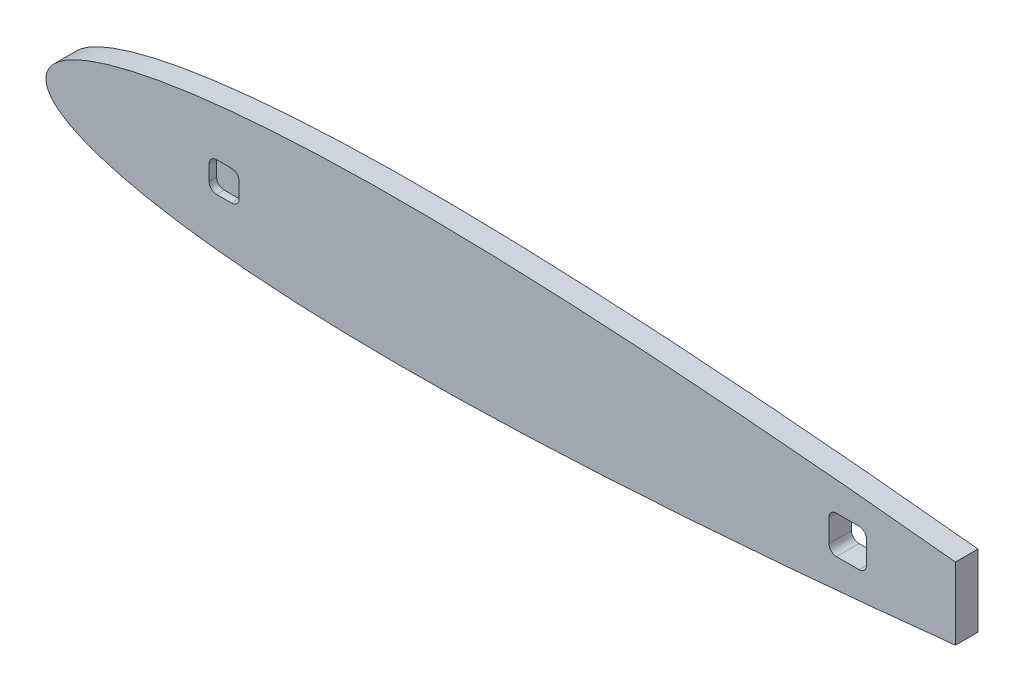
SolidWorks part; units mm, degrees
ref_plane "Plano frontal" through (0, 0, 0) normal (0, 0, 1) x (1, 0, 0)
ref_plane "Plano superior" through (0, 0, 0) normal (0, 1, 0) x (1, 0, 0)
ref_plane "Plano direito" through (0, 0, 0) normal (1, 0, 0) x (0, 0, -1)
curve "1"
  spline degree 3 poles (318.017, -0.275, 0) (321.8619, 0, 0) (318.017, 0.275, 0) (316.8488, 0.4429, 0) (316.2887, 0.5205, 0) (315.3688, 0.6495, 0) (314.0783, 0.829, 0) (312.4264, 1.0569, 0) (310.4146, 1.3335, 0) (308.0483, 1.6557, 0) (305.3328, 2.0216, 0) (302.2747, 2.4296, 0) (298.881, 2.8766, 0) (295.1596, 3.3607, 0) (291.1192, 3.8779, 0) (286.7692, 4.4269, 0) (282.1198, 5.0039, 0) (277.1818, 5.6059, 0) (271.9669, 6.2303, 0) (266.4872, 6.8736, 0) (260.7553, 7.5322, 0) (254.7848, 8.2043, 0) (248.5896, 8.8851, 0) (242.1844, 9.5727, 0) (235.5837, 10.2623, 0) (228.8033, 10.9526, 0) (221.8588, 11.6382, 0) (214.7666, 12.3171, 0) (207.5431, 12.9844, 0) (200.2052, 13.638, 0) (192.77, 14.2725, 0) (185.255, 14.885, 0) (177.6777, 15.4717, 0) (170.0557, 16.0279, 0) (162.407, 16.55, 0) (154.7495, 17.0338, 0) (147.1007, 17.4748, 0) (139.4788, 17.8694, 0) (131.9014, 18.2133, 0) (124.3862, 18.5027, 0) (116.9509, 18.7344, 0) (109.6128, 18.9042, 0) (102.389, 19.0091, 0) (95.2963, 19.0463, 0) (88.3513, 19.0134, 0) (81.5703, 18.9091, 0) (74.9692, 18.7301, 0) (68.5632, 18.4773, 0) (62.3674, 18.1489, 0) (56.396, 17.7457, 0) (50.6632, 17.2678, 0) (45.1824, 16.7162, 0) (39.9662, 16.0928, 0) (35.0266, 15.4003, 0) (30.3754, 14.64, 0) (26.0232, 13.8155, 0) (21.9799, 12.9301, 0) (18.2551, 11.9867, 0) (14.8569, 10.9896, 0) (11.7929, 9.9421, 0) (9.0696, 8.8477, 0) (6.6923, 7.7097, 0) (4.6657, 6.5304, 0) (2.9921, 5.3119, 0) (1.6746, 4.052, 0) (0.7166, 2.7472, 0) (0.1308, 1.3913, 0) (-0.0638, 0, 0) (0.1308, -1.3913, 0) (0.7166, -2.7472, 0) (1.6746, -4.052, 0) (2.9921, -5.3119, 0) (4.6657, -6.5304, 0) (6.6923, -7.7097, 0) (9.0696, -8.8477, 0) (11.7929, -9.9421, 0) (14.8569, -10.9896, 0) (18.2551, -11.9867, 0) (21.9799, -12.9301, 0) (26.0232, -13.8155, 0) (30.3754, -14.64, 0) (35.0266, -15.4003, 0) (39.9662, -16.0928, 0) (45.1824, -16.7162, 0) (50.6632, -17.2678, 0) (56.396, -17.7457, 0) (62.3674, -18.1489, 0) (68.5632, -18.4773, 0) (74.9692, -18.7301, 0) (81.5703, -18.9091, 0) (88.3513, -19.0134, 0) (95.2963, -19.0463, 0) (102.389, -19.0091, 0) (109.6128, -18.9042, 0) (116.9509, -18.7344, 0) (124.3862, -18.5027, 0) (131.9014, -18.2133, 0) (139.4788, -17.8694, 0) (147.1007, -17.4748, 0) (154.7495, -17.0338, 0) (162.407, -16.55, 0) (170.0557, -16.0279, 0) (177.6777, -15.4717, 0) (185.255, -14.885, 0) (192.77, -14.2725, 0) (200.2052, -13.638, 0) (207.5431, -12.9844, 0) (214.7666, -12.3171, 0) (221.8588, -11.6382, 0) (228.8033, -10.9526, 0) (235.5837, -10.2623, 0) (242.1844, -9.5727, 0) (248.5896, -8.8851, 0) (254.7848, -8.2043, 0) (260.7553, -7.5322, 0) (266.4872, -6.8736, 0) (271.9669, -6.2303, 0) (277.1818, -5.6059, 0) (282.1198, -5.0039, 0) (286.7692, -4.4269, 0) (291.1192, -3.8779, 0) (295.1596, -3.3607, 0) (298.881, -2.8766, 0) (302.2747, -2.4296, 0) (305.3328, -2.0216, 0) (308.0483, -1.6557, 0) (310.4146, -1.3335, 0) (312.4264, -1.0569, 0) (314.0783, -0.829, 0) (315.3688, -0.6495, 0) (316.2887, -0.5205, 0) (316.8488, -0.4429, 0) (318.017, -0.275, 0) (321.8619, 0, 0) (318.017, 0.275, 0) knots -0.00555 -0.004691 -0.004405 0 0.004405 0.004691 0.00555 0.00698 0.008976 0.011535 0.014649 0.018312 0.022515 0.027248 0.032498 0.038254 0.044502 0.051227 0.058413 0.066043 0.074099 0.082562 0.091412 0.100627 0.110187 0.120068 0.130247 0.140701 0.151404 0.162332 0.173459 0.184758 0.196204 0.207769 0.219426 0.231148 0.242906 0.254675 0.266426 0.278132 0.289766 0.301302 0.312712 0.323969 0.33505 0.345929 0.356581 0.366982 0.37711 0.386942 0.396458 0.405637 0.414459 0.422907 0.430963 0.438612 0.445838 0.45263 0.458976 0.464866 0.470294 0.475255 0.479749 0.483781 0.487363 0.490516 0.493279 0.495712 0.49791 0.5 0.50209 0.504288 0.506721 0.509484 0.512637 0.516219 0.520251 0.524745 0.529706 0.535134 0.541024 0.54737 0.554162 0.561388 0.569037 0.577093 0.585541 0.594363 0.603542 0.613058 0.62289 0.633018 0.643419 0.654071 0.66495 0.676031 0.687288 0.698698 0.710234 0.721868 0.733574 0.745325 0.757094 0.768852 0.780574 0.792231 0.803796 0.815242 0.826541 0.837668 0.848596 0.859299 0.869753 0.879932 0.889813 0.899373 0.908588 0.917438 0.925901 0.933957 0.941587 0.948773 0.955498 0.961746 0.967502 0.972752 0.977485 0.981688 0.985351 0.988465 0.991024 0.99302 0.99445 0.995309 0.995595 1 1.004405 1.004691 1.00555 periodic
curve "3"
  spline degree 3 poles (285.8178, -0.2472, 0) (289.2733, 0, 0) (285.8178, 0.2472, 0) (284.7679, 0.3981, 0) (284.2644, 0.4678, 0) (283.4377, 0.5838, 0) (282.2778, 0.7451, 0) (280.7932, 0.9499, 0) (278.9851, 1.1985, 0) (276.8584, 1.4881, 0) (274.4179, 1.8169, 0) (271.6694, 2.1836, 0) (268.6193, 2.5853, 0) (265.2747, 3.0204, 0) (261.6434, 3.4852, 0) (257.7338, 3.9787, 0) (253.5551, 4.4973, 0) (249.1172, 5.0383, 0) (244.4303, 5.5995, 0) (239.5054, 6.1777, 0) (234.3538, 6.7696, 0) (228.9879, 7.3736, 0) (223.4199, 7.9855, 0) (217.6632, 8.6035, 0) (211.7309, 9.2233, 0) (205.637, 9.8437, 0) (199.3956, 10.4599, 0) (193.0214, 11.07, 0) (186.5293, 11.6697, 0) (179.9344, 12.2571, 0) (173.2521, 12.8274, 0) (166.4979, 13.3779, 0) (159.6878, 13.9052, 0) (152.8376, 14.4051, 0) (145.9633, 14.8743, 0) (139.0811, 15.3092, 0) (132.2068, 15.7055, 0) (125.3566, 16.0601, 0) (118.5464, 16.3692, 0) (111.7921, 16.6293, 0) (105.1096, 16.8375, 0) (98.5145, 16.9901, 0) (92.0222, 17.0845, 0) (85.6476, 17.1179, 0) (79.4058, 17.0883, 0) (73.3113, 16.9946, 0) (67.3786, 16.8337, 0) (61.6212, 16.6065, 0) (56.0527, 16.3113, 0) (50.6859, 15.9489, 0) (45.5336, 15.5194, 0) (40.6077, 15.0237, 0) (35.9196, 14.4634, 0) (31.4802, 13.841, 0) (27.2999, 13.1577, 0) (23.3883, 12.4167, 0) (19.7544, 11.6209, 0) (16.4067, 10.7731, 0) (13.3526, 9.8769, 0) (10.5989, 8.9355, 0) (8.1513, 7.9519, 0) (6.0147, 6.9291, 0) (4.1933, 5.8692, 0) (2.6891, 4.774, 0) (1.5051, 3.6417, 0) (0.644, 2.4691, 0) (0.1176, 1.2504, 0) (-0.0573, 0, 0) (0.1176, -1.2504, 0) (0.644, -2.4691, 0) (1.5051, -3.6417, 0) (2.6891, -4.774, 0) (4.1933, -5.8692, 0) (6.0147, -6.9291, 0) (8.1513, -7.9519, 0) (10.5989, -8.9355, 0) (13.3526, -9.8769, 0) (16.4067, -10.7731, 0) (19.7544, -11.6209, 0) (23.3883, -12.4167, 0) (27.2999, -13.1577, 0) (31.4802, -13.841, 0) (35.9196, -14.4634, 0) (40.6077, -15.0237, 0) (45.5336, -15.5194, 0) (50.6859, -15.9489, 0) (56.0527, -16.3113, 0) (61.6212, -16.6065, 0) (67.3786, -16.8337, 0) (73.3113, -16.9946, 0) (79.4058, -17.0883, 0) (85.6476, -17.1179, 0) (92.0222, -17.0845, 0) (98.5145, -16.9901, 0) (105.1096, -16.8375, 0) (111.7921, -16.6293, 0) (118.5464, -16.3692, 0) (125.3566, -16.0601, 0) (132.2068, -15.7055, 0) (139.0811, -15.3092, 0) (145.9633, -14.8743, 0) (152.8376, -14.4051, 0) (159.6878, -13.9052, 0) (166.4979, -13.3779, 0) (173.2521, -12.8274, 0) (179.9344, -12.2571, 0) (186.5293, -11.6697, 0) (193.0214, -11.07, 0) (199.3956, -10.4599, 0) (205.637, -9.8437, 0) (211.7309, -9.2233, 0) (217.6632, -8.6035, 0) (223.4199, -7.9855, 0) (228.9879, -7.3736, 0) (234.3538, -6.7696, 0) (239.5054, -6.1777, 0) (244.4303, -5.5995, 0) (249.1172, -5.0383, 0) (253.5551, -4.4973, 0) (257.7338, -3.9787, 0) (261.6434, -3.4852, 0) (265.2747, -3.0204, 0) (268.6193, -2.5853, 0) (271.6694, -2.1836, 0) (274.4179, -1.8169, 0) (276.8584, -1.4881, 0) (278.9851, -1.1985, 0) (280.7932, -0.9499, 0) (282.2778, -0.7451, 0) (283.4377, -0.5838, 0) (284.2644, -0.4678, 0) (284.7679, -0.3981, 0) (285.8178, -0.2472, 0) (289.2733, 0, 0) (285.8178, 0.2472, 0) knots -0.00555 -0.004691 -0.004405 0 0.004405 0.004691 0.00555 0.00698 0.008976 0.011535 0.014649 0.018312 0.022515 0.027248 0.032498 0.038254 0.044502 0.051227 0.058413 0.066043 0.074099 0.082562 0.091412 0.100627 0.110187 0.120068 0.130247 0.140701 0.151404 0.162332 0.173459 0.184758 0.196204 0.207769 0.219426 0.231148 0.242906 0.254675 0.266426 0.278132 0.289766 0.301302 0.312712 0.323969 0.33505 0.345929 0.356581 0.366982 0.37711 0.386942 0.396458 0.405637 0.414459 0.422907 0.430963 0.438612 0.445838 0.45263 0.458976 0.464866 0.470294 0.475255 0.479749 0.483781 0.487363 0.490516 0.493279 0.495712 0.49791 0.5 0.50209 0.504288 0.506721 0.509484 0.512637 0.516219 0.520251 0.524745 0.529706 0.535134 0.541024 0.54737 0.554162 0.561388 0.569037 0.577093 0.585541 0.594363 0.603542 0.613058 0.62289 0.633018 0.643419 0.654071 0.66495 0.676031 0.687288 0.698698 0.710234 0.721868 0.733574 0.745325 0.757094 0.768852 0.780574 0.792231 0.803796 0.815242 0.826541 0.837668 0.848596 0.859299 0.869753 0.879932 0.889813 0.899373 0.908588 0.917438 0.925901 0.933957 0.941587 0.948773 0.955498 0.961746 0.967502 0.972752 0.977485 0.981688 0.985351 0.988465 0.991024 0.99302 0.99445 0.995309 0.995595 1 1.004405 1.004691 1.00555 periodic
sketch "1-3" plane through (0, 0, 0) normal (0, 0, 1) x (1, 0, 0)
  line L0 (320, 0) -> (287.6, 0) construction
  spline S0 degree 3 poles (285.8178, -0.2472) (289.2733, 0) (285.8178, 0.2472) (284.7679, 0.3981) (284.2644, 0.4678) (283.4377, 0.5838) (282.2778, 0.7451) (280.7932, 0.9499) (278.9851, 1.1985) (276.8584, 1.4881) (274.4179, 1.8169) (271.6694, 2.1836) (268.6193, 2.5853) (265.2747, 3.0204) (261.6434, 3.4852) (257.7338, 3.9787) (253.5551, 4.4973) (249.1172, 5.0383) (244.4303, 5.5995) (239.5054, 6.1777) (234.3538, 6.7696) (228.9879, 7.3736) (223.4199, 7.9855) (217.6632, 8.6035) (211.7309, 9.2233) (205.637, 9.8437) (199.3956, 10.4599) (193.0214, 11.07) (186.5293, 11.6697) (179.9344, 12.2571) (173.2521, 12.8274) (166.4979, 13.3779) (159.6878, 13.9052) (152.8376, 14.4051) (145.9633, 14.8743) (139.0811, 15.3092) (132.2068, 15.7055) (125.3566, 16.0601) (118.5464, 16.3692) (111.7921, 16.6293) (105.1096, 16.8375) (98.5145, 16.9901) (92.0222, 17.0845) (85.6476, 17.1179) (79.4058, 17.0883) (73.3113, 16.9946) (67.3786, 16.8337) (61.6212, 16.6065) (56.0527, 16.3113) (50.6859, 15.9489) (45.5336, 15.5194) (40.6077, 15.0237) (35.9196, 14.4634) (31.4802, 13.841) (27.2999, 13.1577) (23.3883, 12.4167) (19.7544, 11.6209) (16.4067, 10.7731) (13.3526, 9.8769) (10.5989, 8.9355) (8.1513, 7.9519) (6.0147, 6.9291) (4.1933, 5.8692) (2.6891, 4.774) (1.5051, 3.6417) (0.644, 2.4691) (0.1176, 1.2504) (-0.0573, 0) (0.1176, -1.2504) (0.644, -2.4691) (1.5051, -3.6417) (2.6891, -4.774) (4.1933, -5.8692) (6.0147, -6.9291) (8.1513, -7.9519) (10.5989, -8.9355) (13.3526, -9.8769) (16.4067, -10.7731) (19.7544, -11.6209) (23.3883, -12.4167) (27.2999, -13.1577) (31.4802, -13.841) (35.9196, -14.4634) (40.6077, -15.0237) (45.5336, -15.5194) (50.6859, -15.9489) (56.0527, -16.3113) (61.6212, -16.6065) (67.3786, -16.8337) (73.3113, -16.9946) (79.4058, -17.0883) (85.6476, -17.1179) (92.0222, -17.0845) (98.5145, -16.9901) (105.1096, -16.8375) (111.7921, -16.6293) (118.5464, -16.3692) (125.3566, -16.0601) (132.2068, -15.7055) (139.0811, -15.3092) (145.9633, -14.8743) (152.8376, -14.4051) (159.6878, -13.9052) (166.4979, -13.3779) (173.2521, -12.8274) (179.9344, -12.2571) (186.5293, -11.6697) (193.0214, -11.07) (199.3956, -10.4599) (205.637, -9.8437) (211.7309, -9.2233) (217.6632, -8.6035) (223.4199, -7.9855) (228.9879, -7.3736) (234.3538, -6.7696) (239.5054, -6.1777) (244.4303, -5.5995) (249.1172, -5.0383) (253.5551, -4.4973) (257.7338, -3.9787) (261.6434, -3.4852) (265.2747, -3.0204) (268.6193, -2.5853) (271.6694, -2.1836) (274.4179, -1.8169) (276.8584, -1.4881) (278.9851, -1.1985) (280.7932, -0.9499) (282.2778, -0.7451) (283.4377, -0.5838) (284.2644, -0.4678) (284.7679, -0.3981) (285.8178, -0.2472) (289.2733, 0) (285.8178, 0.2472) knots -0.00555 -0.004691 -0.004405 0 0.004405 0.004691 0.00555 0.00698 0.008976 0.011535 0.014649 0.018312 0.022515 0.027248 0.032498 0.038254 0.044502 0.051227 0.058413 0.066043 0.074099 0.082562 0.091412 0.100627 0.110187 0.120068 0.130247 0.140701 0.151404 0.162332 0.173459 0.184758 0.196204 0.207769 0.219426 0.231148 0.242906 0.254675 0.266426 0.278132 0.289766 0.301302 0.312712 0.323969 0.33505 0.345929 0.356581 0.366982 0.37711 0.386942 0.396458 0.405637 0.414459 0.422907 0.430963 0.438612 0.445838 0.45263 0.458976 0.464866 0.470294 0.475255 0.479749 0.483781 0.487363 0.490516 0.493279 0.495712 0.49791 0.5 0.50209 0.504288 0.506721 0.509484 0.512637 0.516219 0.520251 0.524745 0.529706 0.535134 0.541024 0.54737 0.554162 0.561388 0.569037 0.577093 0.585541 0.594363 0.603542 0.613058 0.62289 0.633018 0.643419 0.654071 0.66495 0.676031 0.687288 0.698698 0.710234 0.721868 0.733574 0.745325 0.757094 0.768852 0.780574 0.792231 0.803796 0.815242 0.826541 0.837668 0.848596 0.859299 0.869753 0.879932 0.889813 0.899373 0.908588 0.917438 0.925901 0.933957 0.941587 0.948773 0.955498 0.961746 0.967502 0.972752 0.977485 0.981688 0.985351 0.988465 0.991024 0.99302 0.99445 0.995309 0.995595 1 1.004405 1.004691 1.00555 only from (287.6, 0) to (287.6, 0) construction
  spline S1 degree 3 poles (318.017, -0.275) (321.8619, 0) (318.017, 0.275) (316.8488, 0.4429) (316.2887, 0.5205) (315.3688, 0.6495) (314.0783, 0.829) (312.4264, 1.0569) (310.4146, 1.3335) (308.0483, 1.6557) (305.3328, 2.0216) (302.2747, 2.4296) (298.881, 2.8766) (295.1596, 3.3607) (291.1192, 3.8779) (286.7692, 4.4269) (282.1198, 5.0039) (277.1818, 5.6059) (271.9669, 6.2303) (266.4872, 6.8736) (260.7553, 7.5322) (254.7848, 8.2043) (248.5896, 8.8851) (242.1844, 9.5727) (235.5837, 10.2623) (228.8033, 10.9526) (221.8588, 11.6382) (214.7666, 12.3171) (207.5431, 12.9844) (200.2052, 13.638) (192.77, 14.2725) (185.255, 14.885) (177.6777, 15.4717) (170.0557, 16.0279) (162.407, 16.55) (154.7495, 17.0338) (147.1007, 17.4748) (139.4788, 17.8694) (131.9014, 18.2133) (124.3862, 18.5027) (116.9509, 18.7344) (109.6128, 18.9042) (102.389, 19.0091) (95.2963, 19.0463) (88.3513, 19.0134) (81.5703, 18.9091) (74.9692, 18.7301) (68.5632, 18.4773) (62.3674, 18.1489) (56.396, 17.7457) (50.6632, 17.2678) (45.1824, 16.7162) (39.9662, 16.0928) (35.0266, 15.4003) (30.3754, 14.64) (26.0232, 13.8155) (21.9799, 12.9301) (18.2551, 11.9867) (14.8569, 10.9896) (11.7929, 9.9421) (9.0696, 8.8477) (6.6923, 7.7097) (4.6657, 6.5304) (2.9921, 5.3119) (1.6746, 4.052) (0.7166, 2.7472) (0.1308, 1.3913) (-0.0638, 0) (0.1308, -1.3913) (0.7166, -2.7472) (1.6746, -4.052) (2.9921, -5.3119) (4.6657, -6.5304) (6.6923, -7.7097) (9.0696, -8.8477) (11.7929, -9.9421) (14.8569, -10.9896) (18.2551, -11.9867) (21.9799, -12.9301) (26.0232, -13.8155) (30.3754, -14.64) (35.0266, -15.4003) (39.9662, -16.0928) (45.1824, -16.7162) (50.6632, -17.2678) (56.396, -17.7457) (62.3674, -18.1489) (68.5632, -18.4773) (74.9692, -18.7301) (81.5703, -18.9091) (88.3513, -19.0134) (95.2963, -19.0463) (102.389, -19.0091) (109.6128, -18.9042) (116.9509, -18.7344) (124.3862, -18.5027) (131.9014, -18.2133) (139.4788, -17.8694) (147.1007, -17.4748) (154.7495, -17.0338) (162.407, -16.55) (170.0557, -16.0279) (177.6777, -15.4717) (185.255, -14.885) (192.77, -14.2725) (200.2052, -13.638) (207.5431, -12.9844) (214.7666, -12.3171) (221.8588, -11.6382) (228.8033, -10.9526) (235.5837, -10.2623) (242.1844, -9.5727) (248.5896, -8.8851) (254.7848, -8.2043) (260.7553, -7.5322) (266.4872, -6.8736) (271.9669, -6.2303) (277.1818, -5.6059) (282.1198, -5.0039) (286.7692, -4.4269) (291.1192, -3.8779) (295.1596, -3.3607) (298.881, -2.8766) (302.2747, -2.4296) (305.3328, -2.0216) (308.0483, -1.6557) (310.4146, -1.3335) (312.4264, -1.0569) (314.0783, -0.829) (315.3688, -0.6495) (316.2887, -0.5205) (316.8488, -0.4429) (318.017, -0.275) (321.8619, 0) (318.017, 0.275) knots -0.00555 -0.004691 -0.004405 0 0.004405 0.004691 0.00555 0.00698 0.008976 0.011535 0.014649 0.018312 0.022515 0.027248 0.032498 0.038254 0.044502 0.051227 0.058413 0.066043 0.074099 0.082562 0.091412 0.100627 0.110187 0.120068 0.130247 0.140701 0.151404 0.162332 0.173459 0.184758 0.196204 0.207769 0.219426 0.231148 0.242906 0.254675 0.266426 0.278132 0.289766 0.301302 0.312712 0.323969 0.33505 0.345929 0.356581 0.366982 0.37711 0.386942 0.396458 0.405637 0.414459 0.422907 0.430963 0.438612 0.445838 0.45263 0.458976 0.464866 0.470294 0.475255 0.479749 0.483781 0.487363 0.490516 0.493279 0.495712 0.49791 0.5 0.50209 0.504288 0.506721 0.509484 0.512637 0.516219 0.520251 0.524745 0.529706 0.535134 0.541024 0.54737 0.554162 0.561388 0.569037 0.577093 0.585541 0.594363 0.603542 0.613058 0.62289 0.633018 0.643419 0.654071 0.66495 0.676031 0.687288 0.698698 0.710234 0.721868 0.733574 0.745325 0.757094 0.768852 0.780574 0.792231 0.803796 0.815242 0.826541 0.837668 0.848596 0.859299 0.869753 0.879932 0.889813 0.899373 0.908588 0.917438 0.925901 0.933957 0.941587 0.948773 0.955498 0.961746 0.967502 0.972752 0.977485 0.981688 0.985351 0.988465 0.991024 0.99302 0.99445 0.995309 0.995595 1 1.004405 1.004691 1.00555 only from (320, 0) to (320, 0) construction
  spline S2 degree 3 poles (285.8178, -0.2472) (289.2733, 0) (285.8178, 0.2472) (284.7679, 0.3981) (284.2644, 0.4678) (283.4377, 0.5838) (282.2778, 0.7451) (280.7932, 0.9499) (278.9851, 1.1985) (276.8584, 1.4881) (274.4179, 1.8169) (271.6694, 2.1836) (268.6193, 2.5853) (265.2747, 3.0204) (261.6434, 3.4852) (257.7338, 3.9787) (253.5551, 4.4973) (249.1172, 5.0383) (244.4303, 5.5995) (239.5054, 6.1777) (234.3538, 6.7696) (228.9879, 7.3736) (223.4199, 7.9855) (217.6632, 8.6035) (211.7309, 9.2233) (205.637, 9.8437) (199.3956, 10.4599) (193.0214, 11.07) (186.5293, 11.6697) (179.9344, 12.2571) (173.2521, 12.8274) (166.4979, 13.3779) (159.6878, 13.9052) (152.8376, 14.4051) (145.9633, 14.8743) (139.0811, 15.3092) (132.2068, 15.7055) (125.3566, 16.0601) (118.5464, 16.3692) (111.7921, 16.6293) (105.1096, 16.8375) (98.5145, 16.9901) (92.0222, 17.0845) (85.6476, 17.1179) (79.4058, 17.0883) (73.3113, 16.9946) (67.3786, 16.8337) (61.6212, 16.6065) (56.0527, 16.3113) (50.6859, 15.9489) (45.5336, 15.5194) (40.6077, 15.0237) (35.9196, 14.4634) (31.4802, 13.841) (27.2999, 13.1577) (23.3883, 12.4167) (19.7544, 11.6209) (16.4067, 10.7731) (13.3526, 9.8769) (10.5989, 8.9355) (8.1513, 7.9519) (6.0147, 6.9291) (4.1933, 5.8692) (2.6891, 4.774) (1.5051, 3.6417) (0.644, 2.4691) (0.1176, 1.2504) (-0.0573, 0) (0.1176, -1.2504) (0.644, -2.4691) (1.5051, -3.6417) (2.6891, -4.774) (4.1933, -5.8692) (6.0147, -6.9291) (8.1513, -7.9519) (10.5989, -8.9355) (13.3526, -9.8769) (16.4067, -10.7731) (19.7544, -11.6209) (23.3883, -12.4167) (27.2999, -13.1577) (31.4802, -13.841) (35.9196, -14.4634) (40.6077, -15.0237) (45.5336, -15.5194) (50.6859, -15.9489) (56.0527, -16.3113) (61.6212, -16.6065) (67.3786, -16.8337) (73.3113, -16.9946) (79.4058, -17.0883) (85.6476, -17.1179) (92.0222, -17.0845) (98.5145, -16.9901) (105.1096, -16.8375) (111.7921, -16.6293) (118.5464, -16.3692) (125.3566, -16.0601) (132.2068, -15.7055) (139.0811, -15.3092) (145.9633, -14.8743) (152.8376, -14.4051) (159.6878, -13.9052) (166.4979, -13.3779) (173.2521, -12.8274) (179.9344, -12.2571) (186.5293, -11.6697) (193.0214, -11.07) (199.3956, -10.4599) (205.637, -9.8437) (211.7309, -9.2233) (217.6632, -8.6035) (223.4199, -7.9855) (228.9879, -7.3736) (234.3538, -6.7696) (239.5054, -6.1777) (244.4303, -5.5995) (249.1172, -5.0383) (253.5551, -4.4973) (257.7338, -3.9787) (261.6434, -3.4852) (265.2747, -3.0204) (268.6193, -2.5853) (271.6694, -2.1836) (274.4179, -1.8169) (276.8584, -1.4881) (278.9851, -1.1985) (280.7932, -0.9499) (282.2778, -0.7451) (283.4377, -0.5838) (284.2644, -0.4678) (284.7679, -0.3981) (285.8178, -0.2472) (289.2733, 0) (285.8178, 0.2472) knots -0.00555 -0.004691 -0.004405 0 0.004405 0.004691 0.00555 0.00698 0.008976 0.011535 0.014649 0.018312 0.022515 0.027248 0.032498 0.038254 0.044502 0.051227 0.058413 0.066043 0.074099 0.082562 0.091412 0.100627 0.110187 0.120068 0.130247 0.140701 0.151404 0.162332 0.173459 0.184758 0.196204 0.207769 0.219426 0.231148 0.242906 0.254675 0.266426 0.278132 0.289766 0.301302 0.312712 0.323969 0.33505 0.345929 0.356581 0.366982 0.37711 0.386942 0.396458 0.405637 0.414459 0.422907 0.430963 0.438612 0.445838 0.45263 0.458976 0.464866 0.470294 0.475255 0.479749 0.483781 0.487363 0.490516 0.493279 0.495712 0.49791 0.5 0.50209 0.504288 0.506721 0.509484 0.512637 0.516219 0.520251 0.524745 0.529706 0.535134 0.541024 0.54737 0.554162 0.561388 0.569037 0.577093 0.585541 0.594363 0.603542 0.613058 0.62289 0.633018 0.643419 0.654071 0.66495 0.676031 0.687288 0.698698 0.710234 0.721868 0.733574 0.745325 0.757094 0.768852 0.780574 0.792231 0.803796 0.815242 0.826541 0.837668 0.848596 0.859299 0.869753 0.879932 0.889813 0.899373 0.908588 0.917438 0.925901 0.933957 0.941587 0.948773 0.955498 0.961746 0.967502 0.972752 0.977485 0.981688 0.985351 0.988465 0.991024 0.99302 0.99445 0.995309 0.995595 1 1.004405 1.004691 1.00555 only from (287.6, 0) to (287.6, 0)
  spline S3 degree 3 poles (318.017, -0.275) (321.8619, 0) (318.017, 0.275) (316.8488, 0.4429) (316.2887, 0.5205) (315.3688, 0.6495) (314.0783, 0.829) (312.4264, 1.0569) (310.4146, 1.3335) (308.0483, 1.6557) (305.3328, 2.0216) (302.2747, 2.4296) (298.881, 2.8766) (295.1596, 3.3607) (291.1192, 3.8779) (286.7692, 4.4269) (282.1198, 5.0039) (277.1818, 5.6059) (271.9669, 6.2303) (266.4872, 6.8736) (260.7553, 7.5322) (254.7848, 8.2043) (248.5896, 8.8851) (242.1844, 9.5727) (235.5837, 10.2623) (228.8033, 10.9526) (221.8588, 11.6382) (214.7666, 12.3171) (207.5431, 12.9844) (200.2052, 13.638) (192.77, 14.2725) (185.255, 14.885) (177.6777, 15.4717) (170.0557, 16.0279) (162.407, 16.55) (154.7495, 17.0338) (147.1007, 17.4748) (139.4788, 17.8694) (131.9014, 18.2133) (124.3862, 18.5027) (116.9509, 18.7344) (109.6128, 18.9042) (102.389, 19.0091) (95.2963, 19.0463) (88.3513, 19.0134) (81.5703, 18.9091) (74.9692, 18.7301) (68.5632, 18.4773) (62.3674, 18.1489) (56.396, 17.7457) (50.6632, 17.2678) (45.1824, 16.7162) (39.9662, 16.0928) (35.0266, 15.4003) (30.3754, 14.64) (26.0232, 13.8155) (21.9799, 12.9301) (18.2551, 11.9867) (14.8569, 10.9896) (11.7929, 9.9421) (9.0696, 8.8477) (6.6923, 7.7097) (4.6657, 6.5304) (2.9921, 5.3119) (1.6746, 4.052) (0.7166, 2.7472) (0.1308, 1.3913) (-0.0638, 0) (0.1308, -1.3913) (0.7166, -2.7472) (1.6746, -4.052) (2.9921, -5.3119) (4.6657, -6.5304) (6.6923, -7.7097) (9.0696, -8.8477) (11.7929, -9.9421) (14.8569, -10.9896) (18.2551, -11.9867) (21.9799, -12.9301) (26.0232, -13.8155) (30.3754, -14.64) (35.0266, -15.4003) (39.9662, -16.0928) (45.1824, -16.7162) (50.6632, -17.2678) (56.396, -17.7457) (62.3674, -18.1489) (68.5632, -18.4773) (74.9692, -18.7301) (81.5703, -18.9091) (88.3513, -19.0134) (95.2963, -19.0463) (102.389, -19.0091) (109.6128, -18.9042) (116.9509, -18.7344) (124.3862, -18.5027) (131.9014, -18.2133) (139.4788, -17.8694) (147.1007, -17.4748) (154.7495, -17.0338) (162.407, -16.55) (170.0557, -16.0279) (177.6777, -15.4717) (185.255, -14.885) (192.77, -14.2725) (200.2052, -13.638) (207.5431, -12.9844) (214.7666, -12.3171) (221.8588, -11.6382) (228.8033, -10.9526) (235.5837, -10.2623) (242.1844, -9.5727) (248.5896, -8.8851) (254.7848, -8.2043) (260.7553, -7.5322) (266.4872, -6.8736) (271.9669, -6.2303) (277.1818, -5.6059) (282.1198, -5.0039) (286.7692, -4.4269) (291.1192, -3.8779) (295.1596, -3.3607) (298.881, -2.8766) (302.2747, -2.4296) (305.3328, -2.0216) (308.0483, -1.6557) (310.4146, -1.3335) (312.4264, -1.0569) (314.0783, -0.829) (315.3688, -0.6495) (316.2887, -0.5205) (316.8488, -0.4429) (318.017, -0.275) (321.8619, 0) (318.017, 0.275) knots -0.00555 -0.004691 -0.004405 0 0.004405 0.004691 0.00555 0.00698 0.008976 0.011535 0.014649 0.018312 0.022515 0.027248 0.032498 0.038254 0.044502 0.051227 0.058413 0.066043 0.074099 0.082562 0.091412 0.100627 0.110187 0.120068 0.130247 0.140701 0.151404 0.162332 0.173459 0.184758 0.196204 0.207769 0.219426 0.231148 0.242906 0.254675 0.266426 0.278132 0.289766 0.301302 0.312712 0.323969 0.33505 0.345929 0.356581 0.366982 0.37711 0.386942 0.396458 0.405637 0.414459 0.422907 0.430963 0.438612 0.445838 0.45263 0.458976 0.464866 0.470294 0.475255 0.479749 0.483781 0.487363 0.490516 0.493279 0.495712 0.49791 0.5 0.50209 0.504288 0.506721 0.509484 0.512637 0.516219 0.520251 0.524745 0.529706 0.535134 0.541024 0.54737 0.554162 0.561388 0.569037 0.577093 0.585541 0.594363 0.603542 0.613058 0.62289 0.633018 0.643419 0.654071 0.66495 0.676031 0.687288 0.698698 0.710234 0.721868 0.733574 0.745325 0.757094 0.768852 0.780574 0.792231 0.803796 0.815242 0.826541 0.837668 0.848596 0.859299 0.869753 0.879932 0.889813 0.899373 0.908588 0.917438 0.925901 0.933957 0.941587 0.948773 0.955498 0.961746 0.967502 0.972752 0.977485 0.981688 0.985351 0.988465 0.991024 0.99302 0.99445 0.995309 0.995595 1 1.004405 1.004691 1.00555 only from (320, 0) to (320, 0)
  dimension "D1" = 32.4
sketch "Esboço2" plane through (0, 0, 0) normal (0, 0, 1) x (1, 0, 0)
  line L0 (320, 0) -> (242, 0) construction
  line L1 (320, 0) -> (213.3333, 0) construction
  line L2 (242, 9.5891) -> (242, -9.5891)
  line L3 (210.3333, -5) -> (216.3333, -5)
  line L4 (208.3333, -3) -> (208.3333, 3)
  line L5 (210.3333, 5) -> (216.3333, 5)
  line L6 (218.3333, -3) -> (218.3333, 3)
  line L7 (208.3333, -5) -> (218.3333, 5) construction
  line L8 (208.3333, 5) -> (218.3333, -5) construction
  arc A0 (210.3333, -5) -> (208.3333, -3) centre (210.3333, -3) cw
  arc A1 (216.3333, -5) -> (218.3333, -3) centre (216.3333, -3) ccw
  arc A2 (216.3333, 5) -> (218.3333, 3) centre (216.3333, 3) cw
  arc A3 (208.3333, 3) -> (210.3333, 5) centre (210.3333, 3) cw
  arc A4 (242, 9.5891) -> (242, -9.5891) centre (247.5363, 0) ccw construction
  spline S0 degree 3 poles (318.017, -0.275) (321.8619, 0) (318.017, 0.275) (316.8488, 0.4429) (316.2887, 0.5205) (315.3688, 0.6495) (314.0783, 0.829) (312.4264, 1.0569) (310.4146, 1.3335) (308.0483, 1.6557) (305.3328, 2.0216) (302.2747, 2.4296) (298.881, 2.8766) (295.1596, 3.3607) (291.1192, 3.8779) (286.7692, 4.4269) (282.1198, 5.0039) (277.1818, 5.6059) (271.9669, 6.2303) (266.4872, 6.8736) (260.7553, 7.5322) (254.7848, 8.2043) (248.5896, 8.8851) (242.1844, 9.5727) (235.5837, 10.2623) (228.8033, 10.9526) (221.8588, 11.6382) (214.7666, 12.3171) (207.5431, 12.9844) (200.2052, 13.638) (192.77, 14.2725) (185.255, 14.885) (177.6777, 15.4717) (170.0557, 16.0279) (162.407, 16.55) (154.7495, 17.0338) (147.1007, 17.4748) (139.4788, 17.8694) (131.9014, 18.2133) (124.3862, 18.5027) (116.9509, 18.7344) (109.6128, 18.9042) (102.389, 19.0091) (95.2963, 19.0463) (88.3513, 19.0134) (81.5703, 18.9091) (74.9692, 18.7301) (68.5632, 18.4773) (62.3674, 18.1489) (56.396, 17.7457) (50.6632, 17.2678) (45.1824, 16.7162) (39.9662, 16.0928) (35.0266, 15.4003) (30.3754, 14.64) (26.0232, 13.8155) (21.9799, 12.9301) (18.2551, 11.9867) (14.8569, 10.9896) (11.7929, 9.9421) (9.0696, 8.8477) (6.6923, 7.7097) (4.6657, 6.5304) (2.9921, 5.3119) (1.6746, 4.052) (0.7166, 2.7472) (0.1308, 1.3913) (-0.0638, 0) (0.1308, -1.3913) (0.7166, -2.7472) (1.6746, -4.052) (2.9921, -5.3119) (4.6657, -6.5304) (6.6923, -7.7097) (9.0696, -8.8477) (11.7929, -9.9421) (14.8569, -10.9896) (18.2551, -11.9867) (21.9799, -12.9301) (26.0232, -13.8155) (30.3754, -14.64) (35.0266, -15.4003) (39.9662, -16.0928) (45.1824, -16.7162) (50.6632, -17.2678) (56.396, -17.7457) (62.3674, -18.1489) (68.5632, -18.4773) (74.9692, -18.7301) (81.5703, -18.9091) (88.3513, -19.0134) (95.2963, -19.0463) (102.389, -19.0091) (109.6128, -18.9042) (116.9509, -18.7344) (124.3862, -18.5027) (131.9014, -18.2133) (139.4788, -17.8694) (147.1007, -17.4748) (154.7495, -17.0338) (162.407, -16.55) (170.0557, -16.0279) (177.6777, -15.4717) (185.255, -14.885) (192.77, -14.2725) (200.2052, -13.638) (207.5431, -12.9844) (214.7666, -12.3171) (221.8588, -11.6382) (228.8033, -10.9526) (235.5837, -10.2623) (242.1844, -9.5727) (248.5896, -8.8851) (254.7848, -8.2043) (260.7553, -7.5322) (266.4872, -6.8736) (271.9669, -6.2303) (277.1818, -5.6059) (282.1198, -5.0039) (286.7692, -4.4269) (291.1192, -3.8779) (295.1596, -3.3607) (298.881, -2.8766) (302.2747, -2.4296) (305.3328, -2.0216) (308.0483, -1.6557) (310.4146, -1.3335) (312.4264, -1.0569) (314.0783, -0.829) (315.3688, -0.6495) (316.2887, -0.5205) (316.8488, -0.4429) (318.017, -0.275) (321.8619, 0) (318.017, 0.275) knots -0.00555 -0.004691 -0.004405 0 0.004405 0.004691 0.00555 0.00698 0.008976 0.011535 0.014649 0.018312 0.022515 0.027248 0.032498 0.038254 0.044502 0.051227 0.058413 0.066043 0.074099 0.082562 0.091412 0.100627 0.110187 0.120068 0.130247 0.140701 0.151404 0.162332 0.173459 0.184758 0.196204 0.207769 0.219426 0.231148 0.242906 0.254675 0.266426 0.278132 0.289766 0.301302 0.312712 0.323969 0.33505 0.345929 0.356581 0.366982 0.37711 0.386942 0.396458 0.405637 0.414459 0.422907 0.430963 0.438612 0.445838 0.45263 0.458976 0.464866 0.470294 0.475255 0.479749 0.483781 0.487363 0.490516 0.493279 0.495712 0.49791 0.5 0.50209 0.504288 0.506721 0.509484 0.512637 0.516219 0.520251 0.524745 0.529706 0.535134 0.541024 0.54737 0.554162 0.561388 0.569037 0.577093 0.585541 0.594363 0.603542 0.613058 0.62289 0.633018 0.643419 0.654071 0.66495 0.676031 0.687288 0.698698 0.710234 0.721868 0.733574 0.745325 0.757094 0.768852 0.780574 0.792231 0.803796 0.815242 0.826541 0.837668 0.848596 0.859299 0.869753 0.879932 0.889813 0.899373 0.908588 0.917438 0.925901 0.933957 0.941587 0.948773 0.955498 0.961746 0.967502 0.972752 0.977485 0.981688 0.985351 0.988465 0.991024 0.99302 0.99445 0.995309 0.995595 1 1.004405 1.004691 1.00555 only from (320, 0) to (320, 0) construction
  spline S1 degree 3 poles (318.017, -0.275) (321.8619, 0) (318.017, 0.275) (316.8488, 0.4429) (316.2887, 0.5205) (315.3688, 0.6495) (314.0783, 0.829) (312.4264, 1.0569) (310.4146, 1.3335) (308.0483, 1.6557) (305.3328, 2.0216) (302.2747, 2.4296) (298.881, 2.8766) (295.1596, 3.3607) (291.1192, 3.8779) (286.7692, 4.4269) (282.1198, 5.0039) (277.1818, 5.6059) (271.9669, 6.2303) (266.4872, 6.8736) (260.7553, 7.5322) (254.7848, 8.2043) (248.5896, 8.8851) (242.1844, 9.5727) (235.5837, 10.2623) (228.8033, 10.9526) (221.8588, 11.6382) (214.7666, 12.3171) (207.5431, 12.9844) (200.2052, 13.638) (192.77, 14.2725) (185.255, 14.885) (177.6777, 15.4717) (170.0557, 16.0279) (162.407, 16.55) (154.7495, 17.0338) (147.1007, 17.4748) (139.4788, 17.8694) (131.9014, 18.2133) (124.3862, 18.5027) (116.9509, 18.7344) (109.6128, 18.9042) (102.389, 19.0091) (95.2963, 19.0463) (88.3513, 19.0134) (81.5703, 18.9091) (74.9692, 18.7301) (68.5632, 18.4773) (62.3674, 18.1489) (56.396, 17.7457) (50.6632, 17.2678) (45.1824, 16.7162) (39.9662, 16.0928) (35.0266, 15.4003) (30.3754, 14.64) (26.0232, 13.8155) (21.9799, 12.9301) (18.2551, 11.9867) (14.8569, 10.9896) (11.7929, 9.9421) (9.0696, 8.8477) (6.6923, 7.7097) (4.6657, 6.5304) (2.9921, 5.3119) (1.6746, 4.052) (0.7166, 2.7472) (0.1308, 1.3913) (-0.0638, 0) (0.1308, -1.3913) (0.7166, -2.7472) (1.6746, -4.052) (2.9921, -5.3119) (4.6657, -6.5304) (6.6923, -7.7097) (9.0696, -8.8477) (11.7929, -9.9421) (14.8569, -10.9896) (18.2551, -11.9867) (21.9799, -12.9301) (26.0232, -13.8155) (30.3754, -14.64) (35.0266, -15.4003) (39.9662, -16.0928) (45.1824, -16.7162) (50.6632, -17.2678) (56.396, -17.7457) (62.3674, -18.1489) (68.5632, -18.4773) (74.9692, -18.7301) (81.5703, -18.9091) (88.3513, -19.0134) (95.2963, -19.0463) (102.389, -19.0091) (109.6128, -18.9042) (116.9509, -18.7344) (124.3862, -18.5027) (131.9014, -18.2133) (139.4788, -17.8694) (147.1007, -17.4748) (154.7495, -17.0338) (162.407, -16.55) (170.0557, -16.0279) (177.6777, -15.4717) (185.255, -14.885) (192.77, -14.2725) (200.2052, -13.638) (207.5431, -12.9844) (214.7666, -12.3171) (221.8588, -11.6382) (228.8033, -10.9526) (235.5837, -10.2623) (242.1844, -9.5727) (248.5896, -8.8851) (254.7848, -8.2043) (260.7553, -7.5322) (266.4872, -6.8736) (271.9669, -6.2303) (277.1818, -5.6059) (282.1198, -5.0039) (286.7692, -4.4269) (291.1192, -3.8779) (295.1596, -3.3607) (298.881, -2.8766) (302.2747, -2.4296) (305.3328, -2.0216) (308.0483, -1.6557) (310.4146, -1.3335) (312.4264, -1.0569) (314.0783, -0.829) (315.3688, -0.6495) (316.2887, -0.5205) (316.8488, -0.4429) (318.017, -0.275) (321.8619, 0) (318.017, 0.275) knots -0.00555 -0.004691 -0.004405 0 0.004405 0.004691 0.00555 0.00698 0.008976 0.011535 0.014649 0.018312 0.022515 0.027248 0.032498 0.038254 0.044502 0.051227 0.058413 0.066043 0.074099 0.082562 0.091412 0.100627 0.110187 0.120068 0.130247 0.140701 0.151404 0.162332 0.173459 0.184758 0.196204 0.207769 0.219426 0.231148 0.242906 0.254675 0.266426 0.278132 0.289766 0.301302 0.312712 0.323969 0.33505 0.345929 0.356581 0.366982 0.37711 0.386942 0.396458 0.405637 0.414459 0.422907 0.430963 0.438612 0.445838 0.45263 0.458976 0.464866 0.470294 0.475255 0.479749 0.483781 0.487363 0.490516 0.493279 0.495712 0.49791 0.5 0.50209 0.504288 0.506721 0.509484 0.512637 0.516219 0.520251 0.524745 0.529706 0.535134 0.541024 0.54737 0.554162 0.561388 0.569037 0.577093 0.585541 0.594363 0.603542 0.613058 0.62289 0.633018 0.643419 0.654071 0.66495 0.676031 0.687288 0.698698 0.710234 0.721868 0.733574 0.745325 0.757094 0.768852 0.780574 0.792231 0.803796 0.815242 0.826541 0.837668 0.848596 0.859299 0.869753 0.879932 0.889813 0.899373 0.908588 0.917438 0.925901 0.933957 0.941587 0.948773 0.955498 0.961746 0.967502 0.972752 0.977485 0.981688 0.985351 0.988465 0.991024 0.99302 0.99445 0.995309 0.995595 1 1.004405 1.004691 1.00555 only from (320, 0) to (320, 0)
  point P8 (208.3333, 0)
  dimension "D5" = 2
  dimension "D1" = 78
  dimension "D2" = 106.6667
  dimension "D3" = 10
  dimension "D4" = 10
extrude "Ressalto-extrusão1" add sketch "Esboço2" along normal blind 6 contours L2 S1 L4 A3 L5 A2 L6 A1 L3 A0
sketch "Esboço3" plane through (0, 0, 6) normal (0, 0, 1) x (1, 0, 0)
  line L0 (0, 0) -> (47.4, 0) construction
  line L2 (45.4, -4) -> (49.4, -4)
  line L3 (43.4, -2) -> (43.4, 2)
  line L4 (45.4, 4) -> (49.4, 4)
  line L5 (51.4, -2) -> (51.4, 2)
  line L6 (43.4, -4) -> (51.4, 4) construction
  line L7 (43.4, 4) -> (51.4, -4) construction
  arc A0 (45.4, -4) -> (43.4, -2) centre (45.4, -2) cw
  arc A1 (49.4, -4) -> (51.4, -2) centre (49.4, -2) ccw
  arc A2 (49.4, 4) -> (51.4, 2) centre (49.4, 2) cw
  arc A3 (43.4, 2) -> (45.4, 4) centre (45.4, 2) cw
  dimension "D4" = 2
  dimension "D1" = 47.4
  dimension "D2" = 8
  dimension "D3" = 8
extrude "Corte-extrusão1" cut sketch "Esboço3" against normal blind 2
